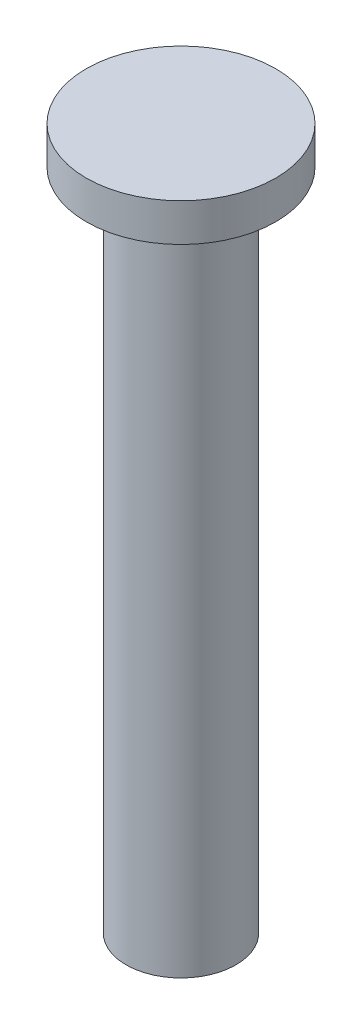
SolidWorks part; units mm, degrees
ref_plane "Front Plane" through (0, 0, 0) normal (0, 0, 1) x (1, 0, 0)
ref_plane "Top Plane" through (0, 0, 0) normal (0, 1, 0) x (1, 0, 0)
ref_plane "Right Plane" through (0, 0, 0) normal (1, 0, 0) x (0, 0, -1)
sketch "Sketch1" plane through (0, 0, 0) normal (0, 0, 1) x (1, 0, 0)
  line L0 (0, 0) -> (0, 37) construction
  line L1 (0, 37) -> (5, 37)
  line L2 (5, 37) -> (5, 35)
  line L3 (5, 35) -> (2.9, 35)
  line L4 (2.9, 35) -> (2.9, 0)
  line L5 (2.9, 0) -> (0, 0)
  line L6 (0, 0) -> (0, 37)
  dimension "D1" = 5.8
  dimension "D2" = 10
  dimension "D3" = 2
  dimension "D4" = 37
revolve "Revolve1" add sketch "Sketch1" angle 360 about L0
